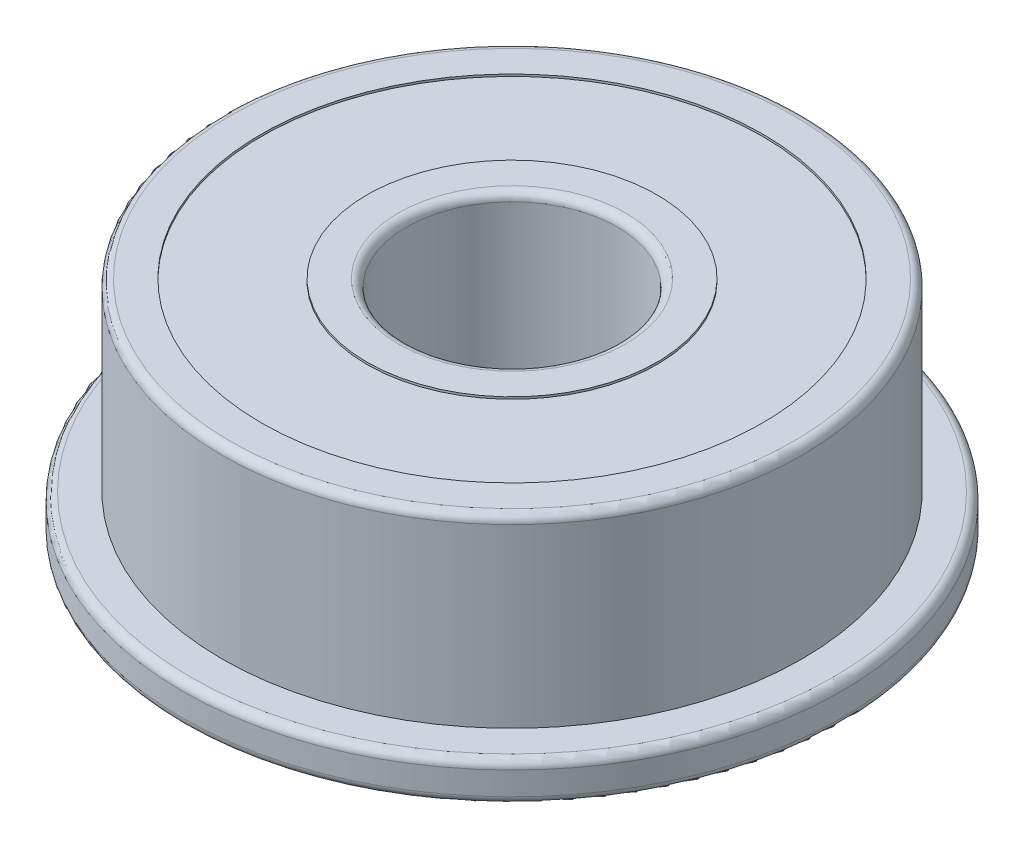
SolidWorks part; units mm, degrees
ref_plane "Front Plane" through (0, 0, 0) normal (0, 0, 1) x (1, 0, 0)
ref_plane "Top Plane" through (0, 0, 0) normal (0, 1, 0) x (1, 0, 0)
ref_plane "Right Plane" through (0, 0, 0) normal (1, 0, 0) x (0, 0, -1)
sketch "Sketch1" plane through (0, 0, 0) normal (0, 1, 0) x (1, 0, 0)
  circle A0 centre (0, 0) radius 12.5
  dimension "D1" = 25
extrude "Boss-Extrude1" add sketch "Sketch1" along normal blind 1.5
sketch "Sketch2" plane through (0, 1.5, 0) normal (0, 1, 0) x (1, 0, 0)
  circle A0 centre (0, 0) radius 11
  dimension "D1" = 22
extrude "Boss-Extrude2" add sketch "Sketch2" along normal blind 7
sketch "Sketch3" plane through (0, 8.5, 0) normal (0, 1, 0) x (1, 0, 0)
  circle A0 centre (0, 0) radius 4
  dimension "D1" = 8
extrude "Cut-Extrude1" cut sketch "Sketch3" against normal through all
sketch "Sketch4" plane through (0, 0, 0) normal (0, -1, 0) x (1, 0, 0)
  circle A0 centre (0, 0) radius 5.5
  circle A1 centre (0, 0) radius 9.5
  dimension "D1" = 19
  dimension "D2" = 11
extrude "Cut-Extrude2" cut sketch "Sketch4" against normal blind 0.08
sketch "Sketch5" plane through (0, 8.5, 0) normal (0, 1, 0) x (1, 0, 0)
  circle A0 centre (0, 0) radius 5.5
  circle A1 centre (0, 0) radius 9.5
  dimension "D1" = 19
  dimension "D2" = 11
extrude "Cut-Extrude3" cut sketch "Sketch5" against normal blind 0.08
fillet "Fillet1" radius 0.31 5 edges at (0, 0, 4) (0, 0, 12.5) (0, 8.5, 11) (0, 8.5, 4) (0, 1.5, 12.5)
